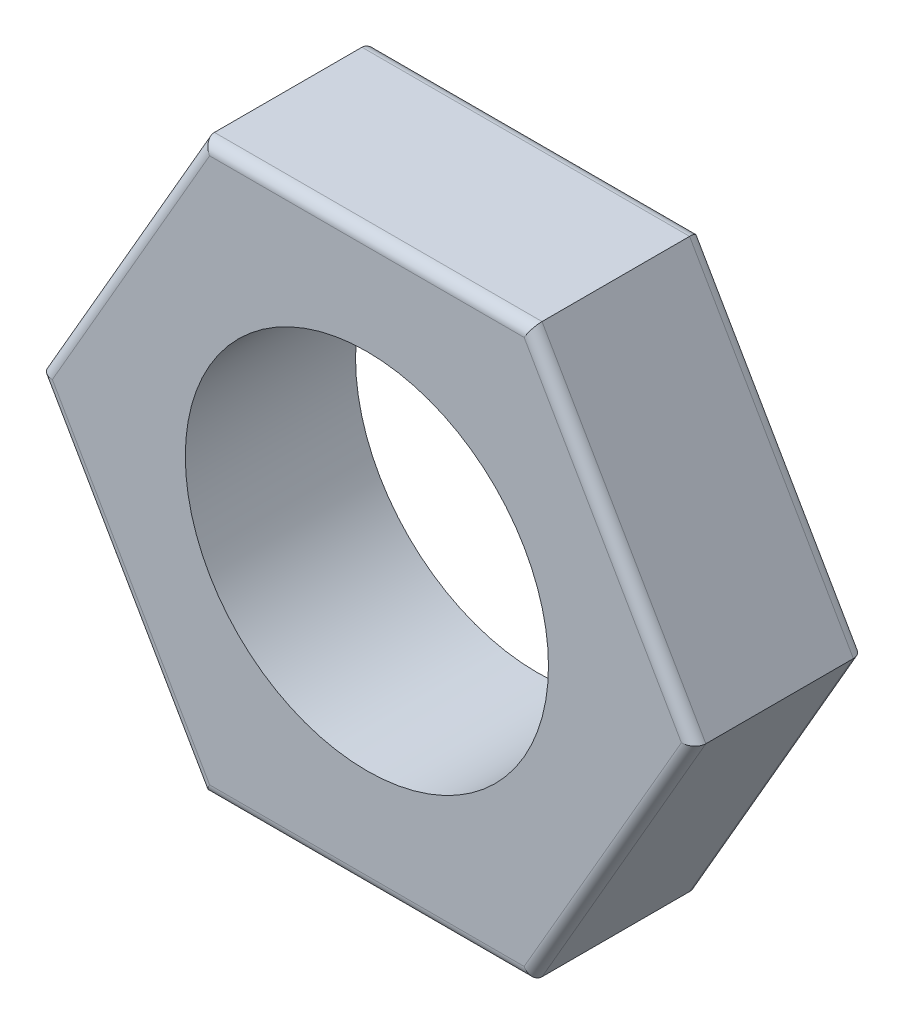
SolidWorks part; units mm, degrees
ref_plane "前视" through (0, 0, 0) normal (0, 0, 1) x (1, 0, 0)
ref_plane "上视" through (0, 0, 0) normal (0, 1, 0) x (1, 0, 0)
ref_plane "右视" through (0, 0, 0) normal (1, 0, 0) x (0, 0, -1)
sketch "草图2" plane through (0, 0, 0) normal (0, 0, 1) x (1, 0, 0)
  line L1 (7.2169, -12.5) -> (14.4338, 0)
  line L2 (14.4338, 0) -> (7.2169, 12.5)
  line L3 (7.2169, 12.5) -> (-7.2169, 12.5)
  line L4 (-7.2169, 12.5) -> (-14.4338, 0)
  line L5 (-14.4338, 0) -> (-7.2169, -12.5)
  line L6 (-7.2169, -12.5) -> (7.2169, -12.5)
  circle A0 centre (0, 0) radius 12.5 construction
  dimension "D1" = 25
extrude "凸台-拉伸1" add sketch "草图2" along normal blind 7.5
sketch "草图3" plane through (0, 0, 7.5) normal (0, 0, 1) x (1, 0, 0)
  circle A0 centre (0, 0) radius 8
  dimension "D1" = 16
extrude "切除-拉伸1" cut sketch "草图3" against normal through all
fillet "圆角1" radius 0.5 12 edges at (-10.8253, 6.25, 7.5) (0, -12.5, 7.5) (-10.8253, -6.25, 7.5) (10.8253, -6.25, 7.5) (10.8253, 6.25, 7.5) (0, 12.5, 7.5) (-10.8253, 6.25, 0) (0, 12.5, 0) (10.8253, 6.25, 0) (10.8253, -6.25, 0) (-10.8253, -6.25, 0) (0, -12.5, 0)
